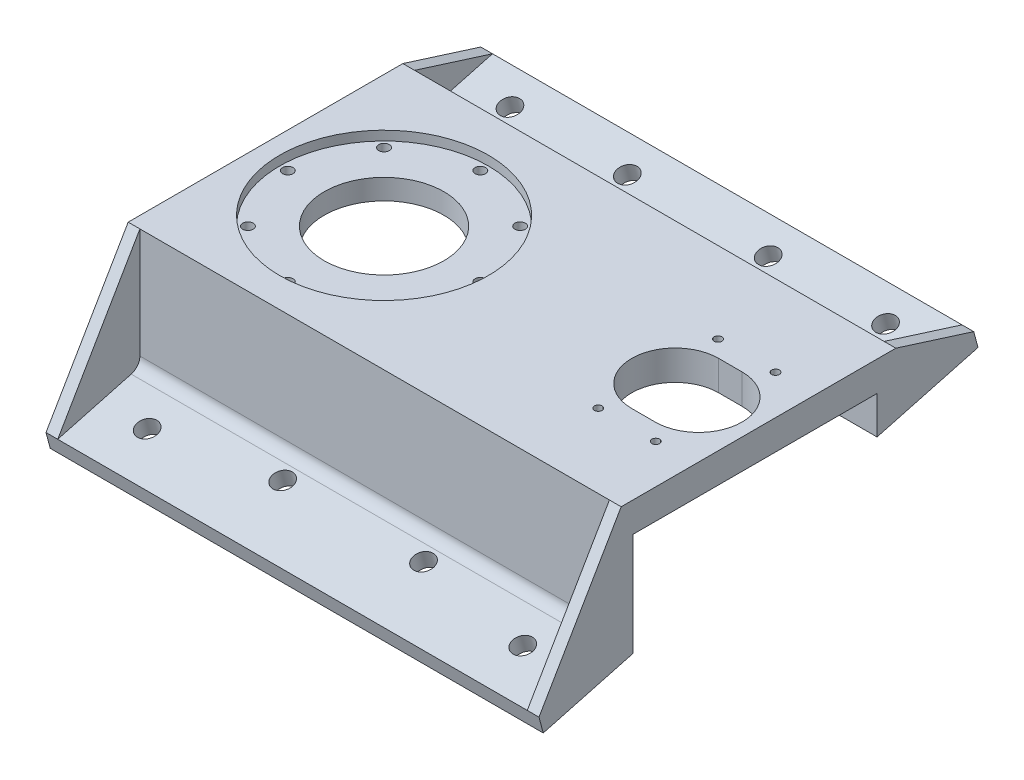
SolidWorks part; units mm, degrees
material "1060 合金"
ref_plane "前视基准面" through (0, 0, 0) normal (0, 0, 1) x (1, 0, 0)
ref_plane "上视基准面" through (0, 0, 0) normal (0, 1, 0) x (1, 0, 0)
ref_plane "右视基准面" through (0, 0, 0) normal (1, 0, 0) x (0, 0, -1)
sketch "草图1" plane through (0, 0, 0) normal (0, 1, 0) x (1, 0, 0)
  line L0 (0, 0) -> (170, 0) construction
  line L1 (170, 31.93) -> (170, -31.93)
  line L2 (15.8391, 73.3084) -> (162.1119, 41.7045)
  line L3 (15.8391, -73.3084) -> (162.1119, -41.7045)
  arc A0 (15.8391, 73.3084) -> (15.8391, -73.3084) centre (0, 0) ccw
  arc A1 (162.1119, -41.7045) -> (170, -31.93) centre (160, -31.93) ccw
  arc A2 (170, 31.93) -> (162.1119, 41.7045) centre (160, 31.93) ccw
  point P6 (170, 0)
  dimension "D1" = 150
  dimension "D4" = 20
  dimension "D5" = 20
  dimension "D2" = 170
  dimension "D3" = 63.86
extrude "凸台-拉伸1" add sketch "草图1" along normal blind 30
sketch "草图2" plane through (0, 30, 0) normal (0, 1, 0) x (1, 0, 0)
  circle A0 centre (0, 0) radius 44.45
  dimension "D1" = 88.9
extrude "切除-拉伸1" cut sketch "草图2" against normal blind 4
sketch "草图3" plane through (0, 26, 0) normal (0, 1, 0) x (1, 0, 0)
  line L0 (0, 0) -> (0, 90.3276) construction
  circle A0 centre (0, 0) radius 25.5
  circle A1 centre (0, 41) radius 2.25
  circle A2 centre (28.9914, 28.9914) radius 2.25
  circle A3 centre (41, 0) radius 2.25
  circle A4 centre (28.9914, -28.9914) radius 2.25
  circle A5 centre (0, -41) radius 2.25
  circle A6 centre (-28.9914, -28.9914) radius 2.25
  circle A7 centre (-41, 0) radius 2.25
  circle A8 centre (-28.9914, 28.9914) radius 2.25
  dimension "D1" = 51
  dimension "D3" = 4.5
  dimension "D2" = 41
  dimension "D4" = 8
extrude "切除-拉伸2" cut sketch "草图3" against normal through all contours A2 | A3 | A4 | A5 | A6 | A7 | A8 | A1 | A0
sketch "草图4" plane through (0, 30, 0) normal (0, 1, 0) x (1, 0, 0)
  line L0 (0, 0) -> (134, 0) construction
  line L1 (124, 18.5) -> (134, 18.5)
  line L2 (124, -18.5) -> (134, -18.5)
  arc A0 (134, -18.5) -> (134, 18.5) centre (134, 0) ccw
  arc A1 (124, 18.5) -> (124, -18.5) centre (124, 0) ccw
  dimension "D2" = 37
  dimension "D3" = 37
  dimension "D1" = 134
  dimension "D4" = 10
extrude "切除-拉伸3" cut sketch "草图4" against normal through all
sketch "草图5" plane through (0, 30, 0) normal (0, 1, 0) x (1, 0, 0)
  arc A0 (134, -18.5) -> (134, 18.5) centre (134, 0) ccw construction
  arc A1 (124, 18.5) -> (124, -18.5) centre (124, 0) ccw construction
  arc A2 (134, -18.5) -> (134, 18.5) centre (134, 0) ccw construction
  arc A3 (124, 18.5) -> (124, -18.5) centre (124, 0) ccw construction
  circle A4 centre (116.75, 25.5) radius 1.65
  circle A5 centre (141.25, 25.5) radius 1.65
  circle A6 centre (141.25, -25.5) radius 1.65
  circle A7 centre (116.75, -25.5) radius 1.65
  dimension "D1" = 3.3
  dimension "D2" = 3.3
  dimension "D3" = 3.3
  dimension "D4" = 3.3
  dimension "D7" = 25.5
  dimension "D5" = 7.25
  dimension "D6" = 25.5
  dimension "D8" = 7.25
  dimension "D9" = 7.25
extrude "切除-拉伸4" cut sketch "草图5" against normal through all
sketch "草图6" plane through (0, 30, 0) normal (0, 1, 0) x (1, 0, 0)
  line L0 (158, 42.5929) -> (158, -42.5929) construction
  line L2 (-52, 54.0463) -> (-52, -54.0463) construction
  line L6 (162.1119, 41.7045) -> (15.8391, 73.3084) construction
  line L7 (15.8391, -73.3084) -> (162.1119, -41.7045) construction
  line L8 (-52, 95) -> (-52, -95)
  line L9 (158, 95) -> (158, -95)
  line L10 (-52, 95) -> (158, 95)
  line L11 (-52, -95) -> (158, -95)
  line L15 (162.1119, 41.7045) -> (15.8391, 73.3084)
  line L16 (15.8391, -73.3084) -> (162.1119, -41.7045)
  line L17 (170, -31.93) -> (170, 31.93)
  line L18 (162.1119, 41.7045) -> (15.8391, 73.3084)
  line L19 (15.8391, -73.3084) -> (162.1119, -41.7045)
  line L20 (170, -31.93) -> (170, 31.93)
  arc A0 (15.8391, 73.3084) -> (15.8391, -73.3084) centre (0, 0) ccw construction
  arc A6 (170, 31.93) -> (162.1119, 41.7045) centre (160, 31.93) ccw
  arc A7 (15.8391, 73.3084) -> (15.8391, -73.3084) centre (0, 0) ccw
  arc A8 (162.1119, -41.7045) -> (170, -31.93) centre (160, -31.93) ccw
  arc A9 (170, 31.93) -> (162.1119, 41.7045) centre (160, 31.93) ccw
  arc A10 (15.8391, 73.3084) -> (15.8391, -73.3084) centre (0, 0) ccw
  arc A11 (162.1119, -41.7045) -> (170, -31.93) centre (160, -31.93) ccw
  point P8 (-52, 0)
  point P13 (158, 0)
  line M26 (162.1119, 41.7045) -> (15.8391, 73.3084)
  arc M27 (15.8391, 73.3084) -> (15.8391, -73.3084) centre (0, 0) ccw
  line M28 (15.8391, -73.3084) -> (162.1119, -41.7045)
  dimension "D3" = 190
  dimension "D1" = 210
  dimension "D2" = 52
  dimension "D4" = 190
  dimension "D5" = 0
extrude "凸台-拉伸2" add sketch "草图6" against normal blind 30 contours L10 L8 L9 M27 M26 | L8 L11 L9 M28 M27
sketch "草图7" plane through (0, 30, 0) normal (0, 1, 0) x (1, 0, 0)
  line L0 (-52, 54.0463) -> (-52, -54.0463)
  line L1 (158, 42.5929) -> (158, -42.5929)
  line L9 (162.1119, 41.7045) -> (158, 42.5929)
  line L10 (158, 42.5929) -> (158, 95)
  line L11 (158, 95) -> (-52, 95)
  line L12 (-52, 95) -> (-52, 54.0463)
  line L13 (-52, -54.0463) -> (-52, -95)
  line L14 (-52, -95) -> (158, -95)
  line L15 (158, -95) -> (158, -42.5929)
  line L16 (158, -42.5929) -> (162.1119, -41.7045)
  line L17 (170, -31.93) -> (170, 31.93)
  line L18 (162.1119, 41.7045) -> (158, 42.5929)
  line L21 (-52, 95) -> (-52, 54.0463)
  line L25 (158, -42.5929) -> (162.1119, -41.7045)
  line L26 (170, -31.93) -> (170, 31.93)
  arc A3 (170, 31.93) -> (162.1119, 41.7045) centre (160, 31.93) ccw
  arc A4 (-52, 54.0463) -> (-52, -54.0463) centre (0, 0) ccw
  arc A5 (162.1119, -41.7045) -> (170, -31.93) centre (160, -31.93) ccw
  arc A6 (170, 31.93) -> (162.1119, 41.7045) centre (160, 31.93) ccw
  arc A7 (-52, 54.0463) -> (-52, -54.0463) centre (0, 0) ccw
  arc A8 (162.1119, -41.7045) -> (170, -31.93) centre (160, -31.93) ccw
  arc M22 (170, 31.93) -> (162.1119, 41.7045) centre (160, 31.93) ccw
  line M23 (162.1119, 41.7045) -> (158, 42.5929)
  arc M27 (-52, 54.0463) -> (-52, -54.0463) centre (0, 0) ccw
  line M31 (158, -42.5929) -> (162.1119, -41.7045)
  arc M32 (162.1119, -41.7045) -> (170, -31.93) centre (160, -31.93) ccw
  line M33 (170, -31.93) -> (170, 31.93)
  dimension "D1" = 0
extrude "切除-拉伸5" cut sketch "草图7" against normal through all contours L0 M27 | L1 M23 M31 M32 M33 M22
sketch "草图9" plane through (-52, 0, 0) normal (-1, 0, 0) x (0, 0, 1)
  line L0 (-95, 20) -> (-60, 10.6218)
  line L1 (-95, 30) -> (95, 30) construction
  line L3 (-60, 10.6218) -> (-60, 30)
  line L5 (-95, 0) -> (-95, 30) construction
  line L7 (-95, 20) -> (-95, 30)
  line L8 (-95, 30) -> (-60, 30)
  dimension "D1" = 15
  dimension "D3" = 19.3782
  dimension "D4" = 35
  dimension "D5" = 10
extrude "切除-拉伸7" cut sketch "草图9" against normal through all contours L8 L3 L0 L7
sketch "草图8" plane through (-52, 0, 0) normal (-1, 0, 0) x (0, 0, 1)
  line L0 (0, 0) -> (52, 0)
  line L1 (-95, 0) -> (95, 0) construction
  line L2 (52, 0) -> (52, 17.3)
  line L3 (52, 17.3) -> (-52, 17.3)
  line L4 (-52, 17.3) -> (-52, 0)
  line L5 (-52, 0) -> (0, 0)
  line L6 (-60, 30) -> (95, 30) construction
  dimension "D1" = 52
  dimension "D2" = 52
  dimension "D3" = 12.7
sketch "草图10" plane through (-52, 0, 0) normal (-1, 0, 0) x (0, 0, 1)
  line L0 (-95, 12.7531) -> (-47.4049, 0) construction
  line L1 (-95, 0) -> (-95, 20) construction
  line L2 (-95, 0) -> (95, 0) construction
  line L3 (-95, 20) -> (-60, 10.6218) construction
  line L6 (-95, 12.7531) -> (-52, 1.2313)
  line L7 (-52, 1.2313) -> (-52, 0)
  line L8 (-95, 12.7531) -> (-95, 0)
  line L9 (-95, 0) -> (-52, 0)
  line L10 (-52, 17.3) -> (-52, 0) construction
  dimension "D1" = 7
extrude "切除-拉伸8" cut sketch "草图10" against normal through all
extrude "切除-拉伸9" cut sketch "草图8" against normal through all
fillet "圆角1" radius 5 1 edges at (53, 10.6218, -60)
sketch "草图11" plane through (-52, 0, 0) normal (-1, 0, 0) x (0, 0, 1)
  line L0 (-95, 12.7531) -> (-93.1883, 19.5145)
  line L1 (-95, 20) -> (-66.2941, 12.3083) construction
  line L2 (-93.1883, 19.5145) -> (-95, 20)
  line L3 (-95, 20) -> (-95, 12.7531)
extrude "切除-拉伸10" cut sketch "草图11" against normal through all
sketch "草图12" plane through (-52, 0, 0) normal (-1, 0, 0) x (0, 0, 1)
  line L0 (-93.1883, 19.5145) -> (-60, 30)
  line L10 (-93.1883, 19.5145) -> (-95, 12.7531)
  line L11 (-95, 12.7531) -> (-52, 1.2313)
  line L12 (-52, 1.2313) -> (-52, 17.3)
  line L13 (-52, 17.3) -> (52, 17.3)
  line L14 (52, 17.3) -> (52, 0)
  line L15 (52, 0) -> (95, 0)
  line L16 (95, 0) -> (95, 30)
  line L17 (95, 30) -> (-60, 30)
  line L18 (-60, 30) -> (-60, 17.1379)
  line L19 (-66.2941, 12.3083) -> (-93.1883, 19.5145)
  line L28 (-60, 30) -> (-60, 17.1379)
  line L29 (-66.2941, 12.3083) -> (-93.1883, 19.5145)
  arc A1 (-66.2941, 12.3083) -> (-60, 17.1379) centre (-65, 17.1379) ccw
  arc A2 (-66.2941, 12.3083) -> (-60, 17.1379) centre (-65, 17.1379) ccw
  dimension "D1" = 0
extrude "凸台-拉伸3" add sketch "草图12" against normal blind 5
sketch "草图13" plane through (158, 0, 0) normal (1, 0, 0) x (0, 0, -1)
  line L3 (66.2941, 12.3083) -> (93.1883, 19.5145)
  line L4 (93.1883, 19.5145) -> (60, 30)
  line L5 (60, 30) -> (60, 17.1379)
  line L6 (66.2941, 12.3083) -> (93.1883, 19.5145)
  line L7 (93.1883, 19.5145) -> (60, 30)
  line L8 (60, 30) -> (60, 17.1379)
  arc A1 (60, 17.1379) -> (66.2941, 12.3083) centre (65, 17.1379) ccw
  arc A2 (60, 17.1379) -> (66.2941, 12.3083) centre (65, 17.1379) ccw
  dimension "D1" = 0
extrude "凸台-拉伸4" add sketch "草图13" against normal blind 5
sketch "草图14" plane through (0, -5.0897, -1.3638) normal (0, 0.9659, 0.2588) x (1, 0, 0)
  line L0 (153, 67.2208) -> (153, 95.0637) construction
  line L3 (153, 95.0637) -> (-47, 95.0637) construction
  circle A0 centre (-27, 82.0637) radius 4.25
  circle A1 centre (23, 82.0637) radius 4.25
  circle A2 centre (83, 82.0637) radius 4.25
  circle A3 centre (133, 82.0637) radius 4.25
  dimension "D1" = 8.5
  dimension "D2" = 160
  dimension "D3" = 20
  dimension "D4" = 50
  dimension "D5" = 50
  dimension "D6" = 13
extrude "切除-拉伸11" cut sketch "草图14" against normal through all
sketch "草图16" plane through (-52, 0, 0) normal (-1, 0, 0) x (0, 0, 1)
  line L0 (-60, 30) -> (95, 30) construction
  line L1 (95, 0) -> (52, 0)
  line L2 (95, 0) -> (95, 30)
  line L3 (95, 30) -> (52, 30)
  line L4 (52, 0) -> (52, 30)
extrude "切除-拉伸12" cut sketch "草图16" against normal through all
ref_plane "基准面1" through (0, -11.8512, -3.1755) normal (0, -0.9659, -0.2588) x (-1, 0, 0)
sketch "草图18" plane through (0, 30, 0) normal (0, 1, 0) x (1, 0, 0)
  line L1 (-52, -52) -> (158, -52)
  line L2 (-52, -52) -> (-52, -57)
  line L3 (-52, -57) -> (158, -57)
  line L4 (158, -52) -> (158, -57)
  dimension "D1" = 5
extrude "凸台-拉伸7" add sketch "草图18" against normal up to surface (56.6355 mm away) up to plane "基准面1"
sketch "草图19" plane through (-52, 0, 0) normal (-1, 0, 0) x (0, 0, 1)
  line L0 (57, -27.9752) -> (90.1883, -36.868)
  line L1 (90.1883, -36.868) -> (92, -30.1065)
  line L2 (92, -30.1065) -> (57, -20.7283)
  line L3 (57, -27.9752) -> (57, 30) construction
  line L4 (57, -20.7283) -> (57, -27.9752)
  line L5 (52, -26.6355) -> (57, -27.9752) construction
  dimension "D1" = 7
  dimension "D2" = 40
extrude "凸台-拉伸8" add sketch "草图19" against normal up to surface (210 mm away) up to face at (158, 8.1654, -14.9098)
sketch "草图20" plane through (-52, 0, 0) normal (-1, 0, 0) x (0, 0, 1)
  line L0 (92, -30.1065) -> (57, -20.7283) construction
  line L1 (57, -20.7283) -> (57, 30) construction
  line L2 (92, -30.1065) -> (57, -20.7283)
  line L3 (57, -20.7283) -> (57, 30)
  line L4 (57, 30) -> (92, -30.1065)
extrude "凸台-拉伸9" add sketch "草图20" against normal blind 5
sketch "草图21" plane through (158, 0, 0) normal (1, 0, 0) x (0, 0, -1)
  line L3 (-57, 30) -> (-92, -30.1065)
  line L4 (-92, -30.1065) -> (-57, -20.7283)
  line L5 (-57, -20.7283) -> (-57, 30)
  line L6 (-57, 30) -> (-92, -30.1065)
  line L7 (-92, -30.1065) -> (-57, -20.7283)
  line L8 (-57, -20.7283) -> (-57, 30)
  dimension "D1" = 0
extrude "凸台-拉伸10" add sketch "草图21" against normal blind 5
sketch "草图22" plane through (0, -5.0897, -1.3638) normal (0, 0.9659, 0.2588) x (1, 0, 0)
  line L0 (-47, -96.6573) -> (-47, -47.2932) construction
  line L2 (153, -96.6573) -> (153, -60.4226) construction
  circle A0 centre (-27, -77.9363) radius 4.25
  circle A1 centre (23, -69.9363) radius 4.25
  circle A2 centre (83, -69.9363) radius 4.25
  circle A3 centre (133, -77.9363) radius 4.25
  circle A4 centre (133, 82.0637) radius 4.25 construction
  circle A5 centre (-27, 82.0637) radius 4.25 construction
  circle A6 centre (23, 82.0637) radius 4.25 construction
  circle A7 centre (83, 82.0637) radius 4.25 construction
  dimension "D1" = 8.5
  dimension "D7" = 152
  dimension "D6" = 152
  dimension "D8" = 50
  dimension "D4" = 160
  dimension "D5" = 160
  dimension "D2" = 20
  dimension "D3" = 20
  dimension "D9" = 50
extrude "切除-拉伸13" cut sketch "草图22" against normal through all
fillet "圆角2" radius 5 1 edges at (53, -20.7283, 57)
